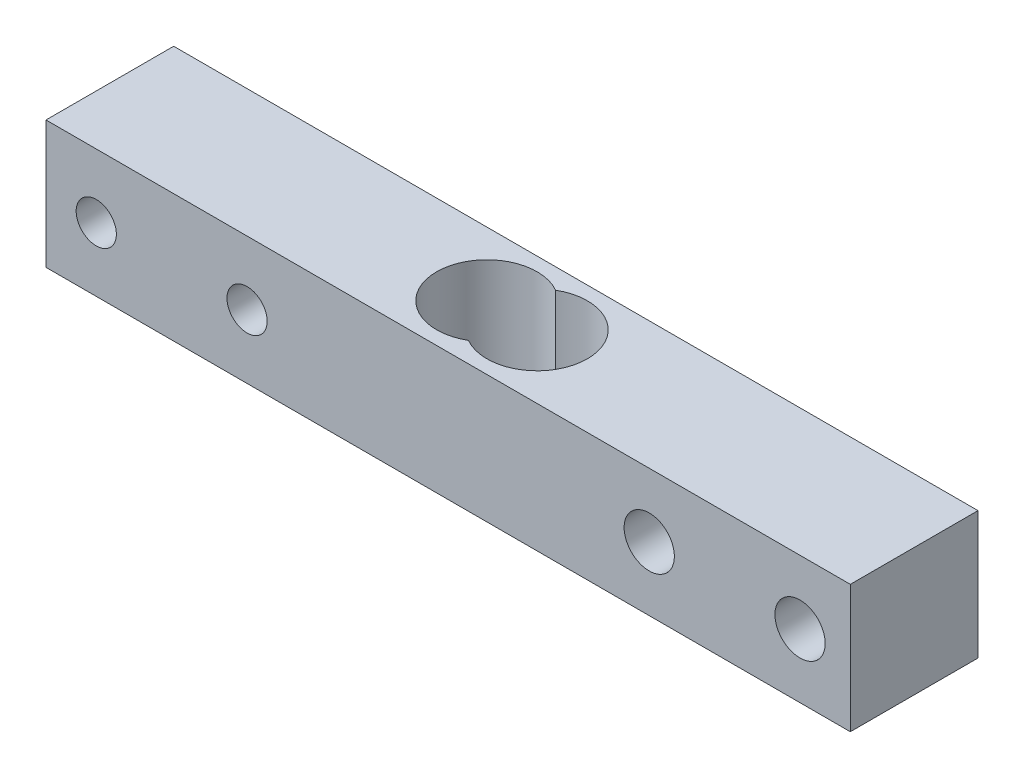
SolidWorks part; units mm, degrees
ref_plane "Front" through (0, 0, 0) normal (0, 0, 1) x (1, 0, 0)
ref_plane "Top" through (0, 0, 0) normal (0, 1, 0) x (1, 0, 0)
ref_plane "Right" through (0, 0, 0) normal (1, 0, 0) x (0, 0, -1)
sketch "Çizim1" plane through (0, 0, 0) normal (0, 0, 1) x (1, 0, 0)
  line L1 (-40, 6.35) -> (40, 6.35)
  line L2 (-40, 6.35) -> (-40, -6.35)
  line L3 (-40, -6.35) -> (40, -6.35)
  line L4 (40, 6.35) -> (40, -6.35)
  line L5 (-40, 6.35) -> (40, -6.35) construction
  line L6 (-40, -6.35) -> (40, 6.35) construction
  point P0 (0, 0)
  dimension "D1" = 80
  dimension "D2" = 12.7
extrude "Yükseklik-Ekstrüzyon1" add sketch "Çizim1" along normal blind 12.7
sketch "Çizim2" plane through (0, 0, 12.7) normal (0, 0, 1) x (1, 0, 0)
  line L0 (40, 0) -> (35, 0)
  line L1 (40, -6.35) -> (40, 6.35) construction
  line L2 (35, 0) -> (20, 0)
  line L3 (-40, 0) -> (-35, 0)
  line L4 (-40, 6.35) -> (-40, -6.35) construction
  line L5 (-35, 0) -> (-20, 0)
  circle A0 centre (35, 0) radius 2.5
  circle A1 centre (20, 0) radius 2.5
  circle A2 centre (-35, 0) radius 2
  circle A3 centre (-20, 0) radius 2
  dimension "D1" = 15
  dimension "D2" = 5
  dimension "D3" = 5
  dimension "D4" = 15
extrude "Kes-Ekstrüzyon1" cut sketch "Çizim2" against normal blind 12.7
sketch "Çizim3" plane through (0, 6.35, 0) normal (0, 1, 0) x (1, 0, 0)
  line L0 (0, 0) -> (0, -2.0199) construction
  line L1 (40, -12.7) -> (-40, -12.7) construction
  line L4 (0, -10.6801) -> (0, -12.7) construction
  arc A0 (0, -2.0199) -> (0, -10.6801) centre (-2.5, -6.35) ccw
  arc A1 (0, -10.6801) -> (0, -2.0199) centre (2.5, -6.35) ccw
extrude "Kes-Ekstrüzyon2" cut sketch "Çizim3" against normal blind 19.7
